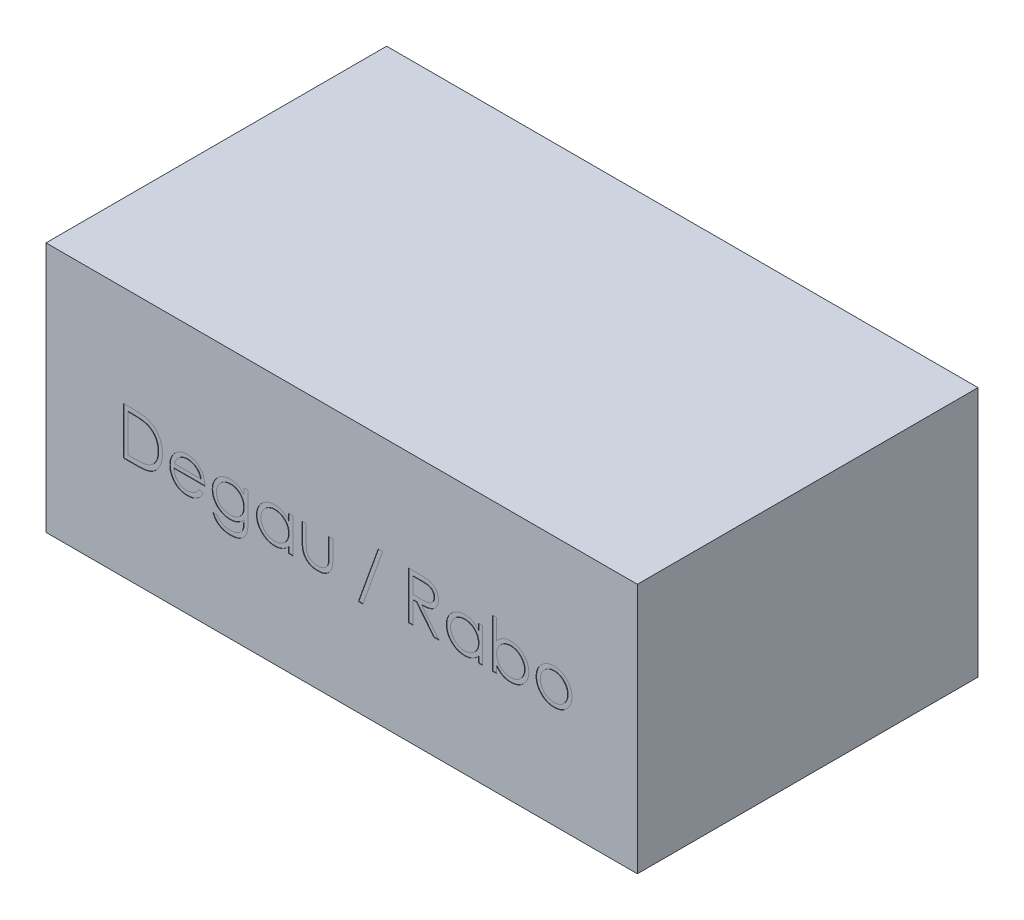
SolidWorks part; units mm, degrees
ref_plane "Front" through (0, 0, 0) normal (0, 0, 1) x (1, 0, 0)
ref_plane "Top" through (0, 0, 0) normal (0, 1, 0) x (1, 0, 0)
ref_plane "Right" through (0, 0, 0) normal (1, 0, 0) x (0, 0, -1)
sketch "Esquisse1" plane through (0, 0, 0) normal (0, 0, 1) x (1, 0, 0)
  line L1 (0, 0) -> (1250, 0)
  line L2 (0, 0) -> (0, 530)
  line L3 (0, 530) -> (1250, 530)
  line L4 (1250, 0) -> (1250, 530)
  dimension "D1" = 1250
  dimension "D2" = 530
extrude "Boss.-Extru.1" add sketch "Esquisse1" along normal blind 720
sketch "Esquisse2" plane through (0, 0, 720) normal (0, 0, 1) x (1, 0, 0)
  text T0 "Degau / Rabo" font "Century Gothic" height 100
extrude "Enlèv. mat.-Extru.1" cut sketch "Esquisse2" against normal blind 1
